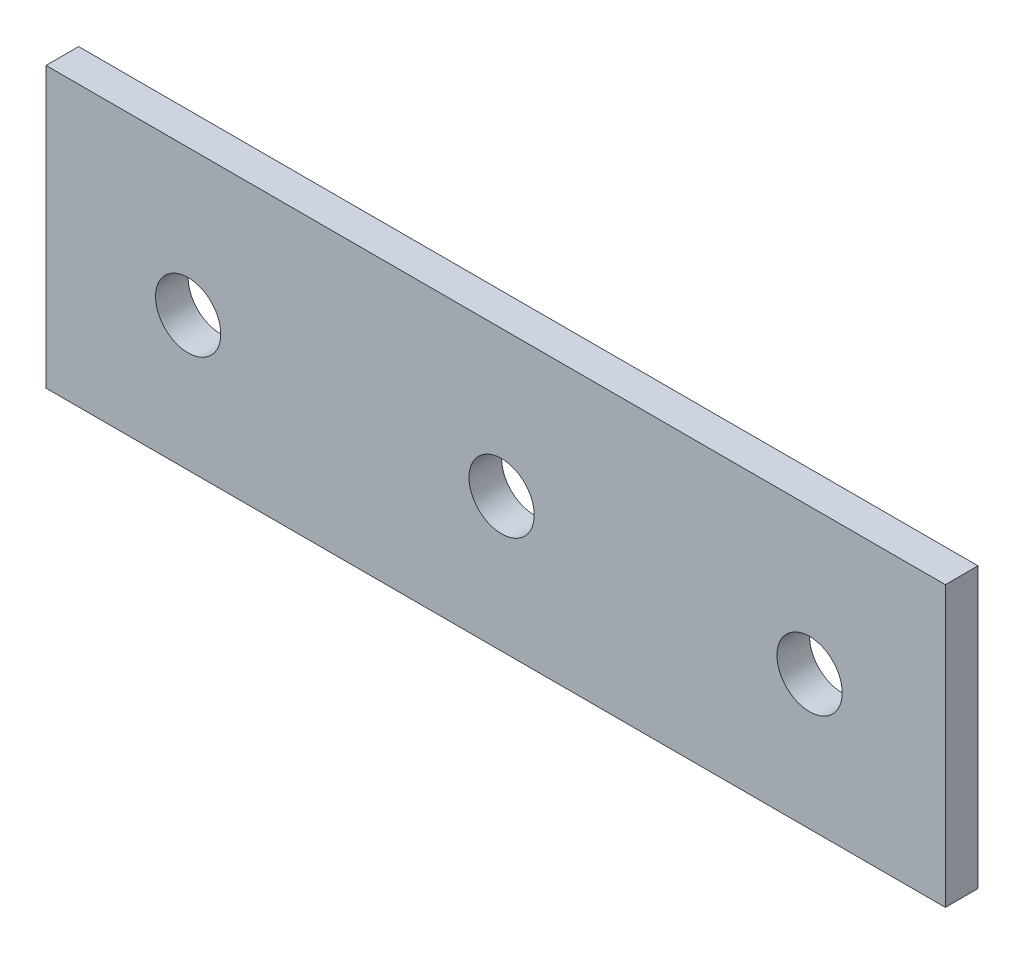
SolidWorks part; units mm, degrees
ref_plane "Front Plane" through (0, 0, 0) normal (0, 0, 1) x (1, 0, 0)
ref_plane "Top Plane" through (0, 0, 0) normal (0, 1, 0) x (1, 0, 0)
ref_plane "Right Plane" through (0, 0, 0) normal (1, 0, 0) x (0, 0, -1)
other "Configuration Table"
sketch "Sketch1" plane through (0, 0, 0) normal (0, 0, 1) x (1, 0, 0)
  line L1 (-101.6187, 53.5918) -> (173.9615, 53.5918)
  line L2 (-101.6187, 53.5918) -> (-101.6187, -32.0583)
  line L3 (-101.6187, -32.0583) -> (173.9615, -32.0583)
  line L4 (173.9615, 53.5918) -> (173.9615, -32.0583)
  circle A0 centre (-58.0678, 9.0731) radius 10
  circle A1 centre (37.986, 9.0731) radius 10
  circle A2 centre (132.3462, 9.0731) radius 10
  dimension "D1" = 20
extrude "Boss-Extrude1" add sketch "Sketch1" along normal blind 10
